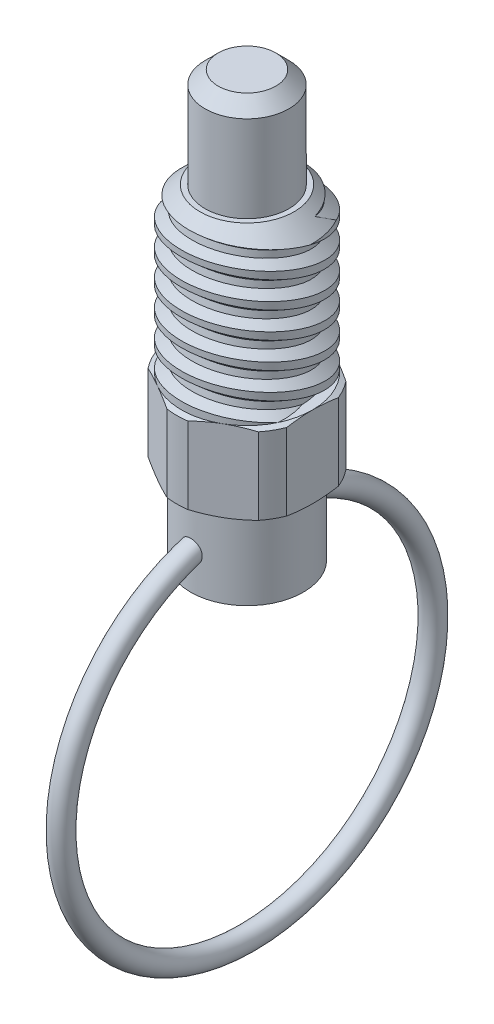
SolidWorks part; units mm, degrees
ref_plane "Front" through (0, 0, 0) normal (0, 0, 1) x (1, 0, 0)
ref_plane "Top" through (0, 0, 0) normal (0, 1, 0) x (1, 0, 0)
ref_plane "Right" through (0, 0, 0) normal (1, 0, 0) x (0, 0, -1)
sketch "Sketch24" plane through (0, 0, 0) normal (1, 0, 0) x (0, 0, -1)
  line L0 (3.175, 3.937) -> (-3.175, 3.937) construction
  line L1 (0, 3.937) -> (3.175, 3.937)
  line L2 (0, 3.937) -> (0, -3.937)
  line L3 (0, -3.937) -> (3.175, -3.937)
  line L4 (3.175, 3.937) -> (3.175, -3.937)
  dimension "Body Length" = 7.874
  dimension "Screw Dia" = 6.35
revolve "Revolve1" add sketch "Sketch24" angle 360 about L2
sketch "Sketch6" plane through (0, 0, 0) normal (1, 0, 0) x (0, 0, -1)
  line L0 (-3.175, 3.937) -> (3.175, 3.937) construction
  line L1 (0.2727, 3.937) -> (-0.2727, 1.21) construction
  line L3 (3.175, 3.937) -> (3.175, 2.667) construction
  line L4 (3.175, 2.667) -> (-3.175, 3.937) construction
  line L5 (-3.175, 3.937) -> (-3.2061, 3.7813) construction
  line L6 (-3.2061, 3.7813) -> (-3.4241, 2.6917)
  line L7 (-3.2061, 3.7813) -> (-2.6099, 3.2574)
  line L8 (-2.6099, 3.2574) -> (-2.6722, 2.946)
  line L10 (-2.6722, 2.946) -> (-3.4241, 2.6917)
  line L13 (-3.175, 3.2085) -> (3.175, 1.9385) construction
  line L15 (3.175, 3.937) -> (3.175, -3.937) construction
  line L22 (-3.175, 3.937) -> (-3.175, -3.937) construction
  point P4 (0, 2.5735)
  point P5 (0, 2.5735)
  point P16 (-2.641, 3.1017)
  dimension "D1" = 1.27
  dimension "D2" = 0.3175
  dimension "D3" = 60
  dimension "D4" = 0.1588
  dimension "Pitch" = 1.27
revolve "Cut-Revolve8" cut sketch "Sketch6" angle 360 about L1
pattern_linear "LPattern1" count 6 spacing 1.27 along (0, -1, 0) count 2 spacing 1.27 along (0, 1, 0) of "Cut-Revolve8"
sketch "Sketch26" plane through (0, 0, 0) normal (1, 0, 0) x (0, 0, -1)
  line L0 (0, -3.1496) -> (0, 3.937)
  line L1 (0, 3.937) -> (0, -3.937) construction
  line L2 (0, 3.937) -> (2.032, 3.937)
  line L3 (2.032, 3.937) -> (2.032, -3.1496)
  line L4 (0, -3.1496) -> (0, -3.937) construction
  line L5 (2.032, -3.1496) -> (0, -3.1496)
  line L7 (2.032, 3.937) -> (-2.032, 3.937) construction
  line L8 (3.175, 3.937) -> (-3.175, 3.937) construction
  point P2 (0, -3.5433)
  dimension "D1" = 0.7874
  dimension "Nose Dia" = 4.064
revolve "Cut-Revolve10" cut sketch "Sketch26" angle 360 about L0
sketch "Sketch31" plane through (0, 0, 0) normal (1, 0, 0) x (0, 0, -1)
  line L1 (3.175, 3.937) -> (3.175, -3.937) construction
  line L3 (0, -3.937) -> (3.175, -3.937) construction
  line L5 (0, 0) -> (3.175, 0) construction
  line L6 (2.286, 3.937) -> (2.286, -3.937) construction
  line L8 (2.032, 3.937) -> (2.032, -3.1496) construction
  line L14 (3.175, 3.937) -> (2.286, 3.937)
  line L15 (0, 3.937) -> (3.175, 3.937) construction
  line L16 (2.286, 3.937) -> (3.175, 3.048)
  line L17 (3.175, 3.048) -> (3.175, 3.937)
  dimension "D1" = 0.254
  dimension "D2" = 45
revolve "Cut-Revolve13" cut sketch "Sketch31" angle 360 about L2
sketch "Sketch27" plane through (0, 0, 0) normal (1, 0, 0) x (0, 0, -1)
  line L0 (0, 3.937) -> (0, -3.937) construction
  line L1 (2.032, 3.937) -> (2.032, -3.1496) construction
  line L2 (0, -3.937) -> (0, 3.4925) construction
  line L3 (0, 8.763) -> (0, 3.4925) construction
  line L4 (2.032, 8.763) -> (2.032, 3.048)
  line L5 (0, 8.763) -> (2.032, 8.763)
  line L6 (0, 3.4925) -> (0, 8.763)
  line L7 (0, 3.937) -> (3.175, 3.937) construction
  line L9 (0, 3.4925) -> (0, 3.048) construction
  line L10 (0, 3.048) -> (2.032, 3.048)
  line L11 (0, 3.937) -> (0, 3.048) construction
  line L12 (0, 3.4925) -> (0, 3.048)
  dimension "Nose Lg" = 4.826
revolve "Revolve2" add sketch "Sketch27" angle 360 about L3
sketch "Sketch36" plane through (0, 0, 0) normal (0, 0, 1) x (1, 0, 0)
  line L1 (-2.7187, 2.667) -> (-3.2385, 2.667)
  line L2 (-2.7187, 2.667) -> (-2.7187, -2.667)
  line L3 (-2.7187, -2.667) -> (-3.2385, -2.667)
  line L4 (-3.2385, 2.667) -> (-3.2385, -2.667)
  line L5 (-2.6933, 0.1891) -> (-2.6933, -0.1222) construction
  line L7 (0, 3.937) -> (0, -3.937) construction
  point P6 (-2.7187, 0)
  dimension "D1" = 3.2385
  dimension "D2" = 0.0254
  dimension "D3" = 1.27
revolve "Revolve3" add sketch "Sketch36" angle 75 mid plane about L2
sketch "Sketch21" plane through (0, 0, 0) normal (1, 0, 0) x (0, 0, -1)
  line L0 (0, -0.0984) -> (0, -0.689) construction
  line L1 (0.7382, -0.3937) -> (-0.7382, -0.3937) construction
  line L3 (0, 3.937) -> (0, -3.937) construction
  line L4 (0, -3.937) -> (3.175, -3.937) construction
  arc A2 (0.4355, 0.3371) -> (-0.4355, 0.3371) centre (0, -0.0984) ccw
  arc A3 (0.4355, -1.1245) -> (-0.4355, -1.1245) centre (0, -0.689) cw
  arc A4 (0.4355, -1.1245) -> (0.4355, 0.3371) centre (-0.2953, -0.3937) ccw
  arc A5 (-0.4355, 0.3371) -> (-0.4355, -1.1245) centre (0.2953, -0.3937) ccw
  point P21 (0, -0.3937)
  dimension "D2" = 0.5906
  dimension "D3" = 3.5433
  dimension "D1" = 1.4764
  dimension "D4" = 0.5906
extrude "Cut-Extrude12" cut sketch "Sketch21" against normal through all flip side to cut
combine bodies "Combine4" operation type add bodies to combine 165 183
sketch "Sketch38" plane through (0, 0, 0) normal (1, 0, 0) x (0, 0, -1)
  line L0 (0, 3.937) -> (3.175, 3.937) construction
  line L1 (0, -3.937) -> (2.7305, -3.937)
  line L2 (0, -3.937) -> (0, -11.811)
  line L3 (0, -11.811) -> (2.7305, -11.811)
  line L4 (2.7305, -3.937) -> (2.7305, -11.811)
  line L6 (2.286, -3.937) -> (3.175, -3.937) construction
  point P5 (0, -7.874)
  dimension "D1" = 2.7305
  dimension "Total Lg" = 15.748
revolve "Revolve4" add sketch "Sketch38" angle 360 about L2
sketch "Sketch42" plane through (0, -3.937, 0) normal (0, -1, 0) x (1, 0, 0)
  line L1 (0, 3.6662) -> (-3.175, 1.8331)
  line L2 (-3.175, 1.8331) -> (-3.175, -1.8331)
  line L3 (-3.175, -1.8331) -> (0, -3.6662)
  line L4 (0, -3.6662) -> (3.175, -1.8331)
  line L5 (3.175, -1.8331) -> (3.175, 1.8331)
  line L6 (3.175, 1.8331) -> (0, 3.6662)
  circle A0 centre (0, 0) radius 3.175 construction
extrude "Extrude1" add sketch "Sketch42" along normal up to vertex (3.937 mm away) up to point (0, -7.874, 0)
sketch "Sketch43" plane through (0, 0, 0) normal (1, 0, 0) x (0, 0, -1)
  line L0 (-3.6662, -3.937) -> (-3.175, -3.937)
  line L1 (-1.8331, -3.937) -> (-3.6662, -3.937) construction
  line L2 (-3.175, -3.937) -> (-3.4122, -4.0476)
  line L3 (-3.4122, -4.0476) -> (-3.4122, -7.7634)
  line L4 (-3.4122, -7.7634) -> (-3.175, -7.874)
  line L5 (-3.6662, -7.874) -> (-1.8331, -7.874) construction
  line L6 (-3.175, -7.874) -> (-3.6662, -7.874)
  line L7 (-3.6662, -7.874) -> (-3.6662, -3.937)
  dimension "D1" = 0.254
  dimension "D2" = 25
revolve "Cut-Revolve15" cut sketch "Sketch43" angle 360 about L2
sketch "Sketch39" plane through (0, 0, 0) normal (0, 0, 1) x (1, 0, 0)
  line L1 (2.0479, -9.656) -> (0, -9.656) construction
  line L3 (1.0239, -9.656) -> (0, -9.656) construction
  line L4 (0, -9.144) -> (0, -28.194) construction
  line L5 (15.6895, -18.669) -> (-15.6895, -18.669) construction
  line L6 (0, -3.937) -> (0, -11.811) construction
  circle A0 centre (0, -9.656) radius 0.512
  point P5 (0, -18.669)
  point P9 (0.512, -9.656)
  point P12 (0, -18.669)
  dimension "D1" = 2.0479
  dimension "Handle" = 19.05
  dimension "D2" = 1.27
revolve "Cut-Revolve14" cut sketch "Sketch39" angle 360 about L5
sketch "Sketch40" plane through (0, 0, 0) normal (1, 0, 0) x (0, 0, -1)
  line L1 (0, -9.144) -> (0, -28.194) construction
  circle A0 centre (0, -18.669) radius 9.525
  dimension "D1" = 19.05
sketch "Sketch41" plane through (0, 0, 0) normal (0, 0, 1) x (1, 0, 0)
  circle A0 centre (0, -9.656) radius 0.512
revolve "Revolve5" add sketch "Sketch41" angle 360 about L5
chamfer "Chamfer1" distance 0.635 angle 45 1 edges at (0, 8.763, 2.032)
equation "\"D2@Sketch6\"=\"Pitch@Sketch6\"/4"
equation "\"D4@Sketch6\"=\"Pitch@Sketch6\"/8"
equation "\"D1@Sketch6\"=\"Pitch@Sketch6\""
equation "\"D3@LPattern1\"=\"Pitch@Sketch6\""
equation "\"D1@LPattern1\"=\"Body Length@Sketch24\"/\"Pitch@Sketch6\""
equation "\"D4@LPattern1\"=\"Pitch@Sketch6\""
equation "\"D1@Sketch21\" = \"Body Length@Sketch24\"*0.1875"
equation "\"D2@Sketch21\" = \"Body Length@Sketch24\"*.075"
equation "\"D3@Sketch21\" = \"Body Length@Sketch24\"*.45"
equation "\"D4@Sketch21\" = \"D2@Sketch21\""
equation "\"D1@Sketch26\" = \"Body Length@Sketch24\"*.1"
equation "\"D1@Sketch40\" = \"Handle@Sketch39\""
equation "\"D1@Sketch39\" = \"D1@Sketch38\"*.75"
